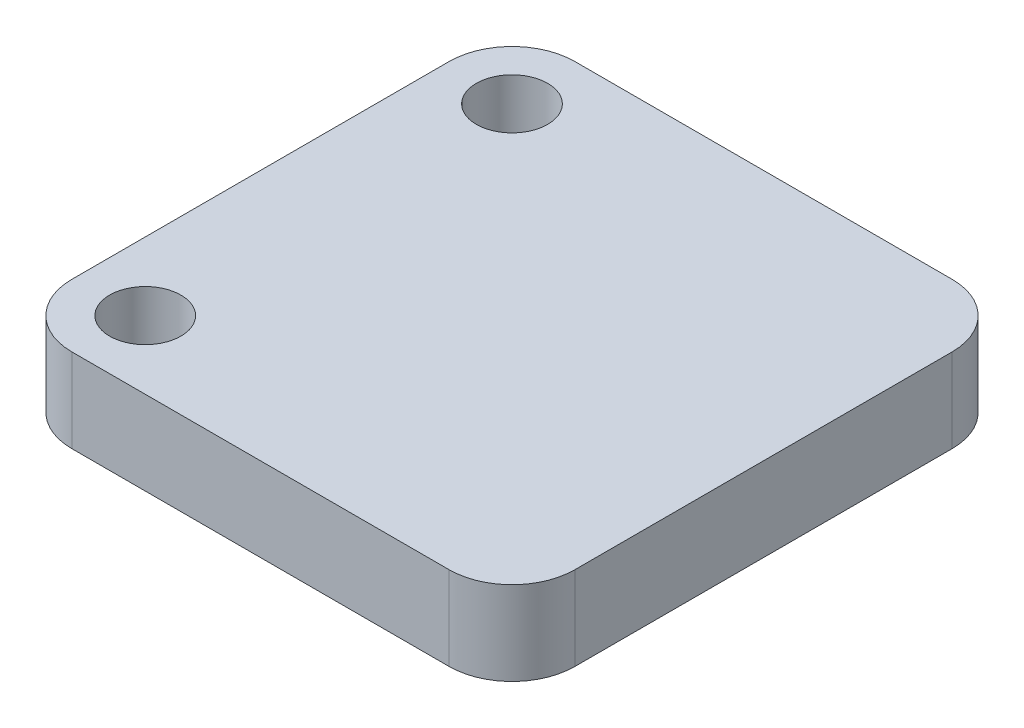
SolidWorks part; units mm, degrees
ref_plane "Plan de face" through (0, 0, 0) normal (0, 0, 1) x (1, 0, 0)
ref_plane "Plan de dessus" through (0, 0, 0) normal (0, 1, 0) x (1, 0, 0)
ref_plane "Plan de droite" through (0, 0, 0) normal (1, 0, 0) x (0, 0, -1)
sketch "Esquisse1" plane through (0, 0, 0) normal (0, 1, 0) x (1, 0, 0)
  line L1 (-12, 12) -> (12, 12)
  line L2 (-12, 12) -> (-12, -12)
  line L3 (-12, -12) -> (12, -12)
  line L4 (12, 12) -> (12, -12)
  line L5 (-12, 12) -> (12, -12) construction
  line L6 (-12, -12) -> (12, 12) construction
  point P0 (0, 0)
  dimension "D1" = 24
extrude "Boss.-Extru.1" add sketch "Esquisse1" along normal blind 4
hole_wizard "Dégagement M31" positions "Esquisse2" profile "Esquisse3" hole size "M3" standard "Ansi Metric" end condition through all
sketch "Esquisse2" plane through (0, 4, 0) normal (0, 1, 0) x (1, 0, 0)
  line L0 (0, 0) -> (-8.75, 0) construction
  line L2 (-8.75, 8.75) -> (-8.75, -8.75) construction
  point P6 (-8.75, 8.75)
  point P7 (-8.75, -8.75)
  dimension "D1" = 17.5
  dimension "D2" = 8.75
sketch "Esquisse3" plane through (-8.75, 4, 8.75) normal (1, 0, 0) x (0, 0, 1)
  line L0 (0, 0) -> (0, 4)
  line L1 (0, 4) -> (1.7, 4)
  line L2 (1.7, 4) -> (1.7, 0)
  line L5 (1.7, 0) -> (0, 0)
  line L11 (0, -6.35) -> (0, 107.95) construction
  dimension "Diamètre du perçage jusqu'au prochain" = 3.4
  dimension "Profondeur du perçage jusqu'au prochain" = 4
fillet "Congé1" radius 3 4 edges at (12, 2, 12) (12, 2, -12) (-12, 2, -12) (-12, 2, 12)
